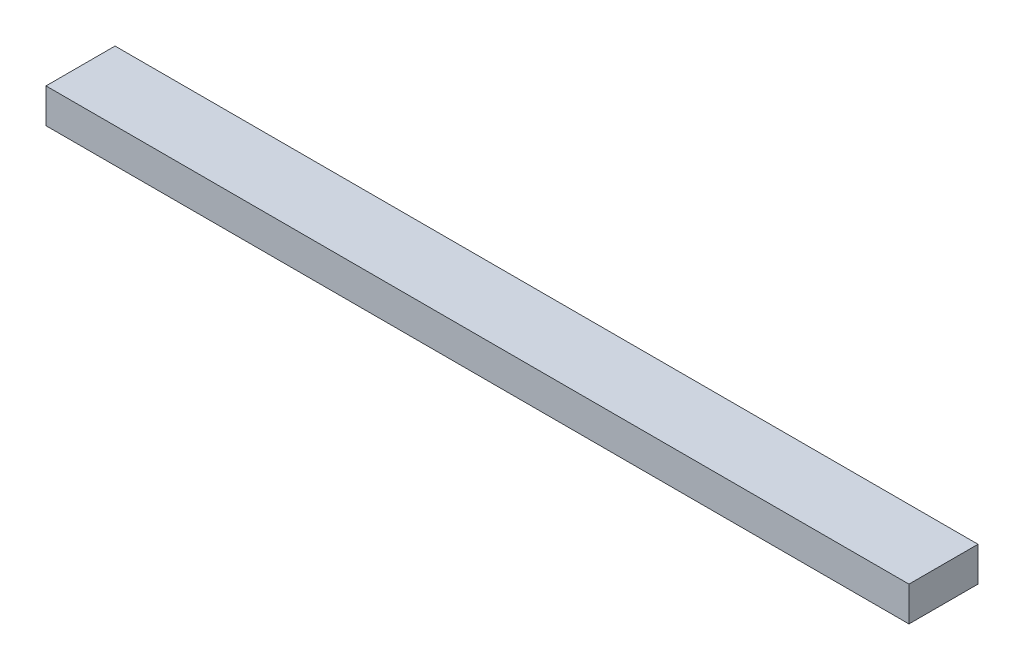
SolidWorks part; units mm, degrees
ref_plane "Plan de face" through (0, 0, 0) normal (0, 0, 1) x (1, 0, 0)
ref_plane "Plan de dessus" through (0, 0, 0) normal (0, 1, 0) x (1, 0, 0)
ref_plane "Plan de droite" through (0, 0, 0) normal (1, 0, 0) x (0, 0, -1)
sketch "Esquisse1" plane through (0, 0, 0) normal (0, 0, 1) x (1, 0, 0)
  line L1 (-25, -1) -> (25, -1)
  line L2 (-25, -1) -> (-25, 1)
  line L3 (-25, 1) -> (25, 1)
  line L4 (25, -1) -> (25, 1)
  line L5 (-25, -1) -> (25, 1) construction
  line L6 (-25, 1) -> (25, -1) construction
  point P0 (0, 0)
  dimension "D1" = 50
  dimension "D2" = 2
extrude "Boss.-Extru.1" add sketch "Esquisse1" along normal blind 4
